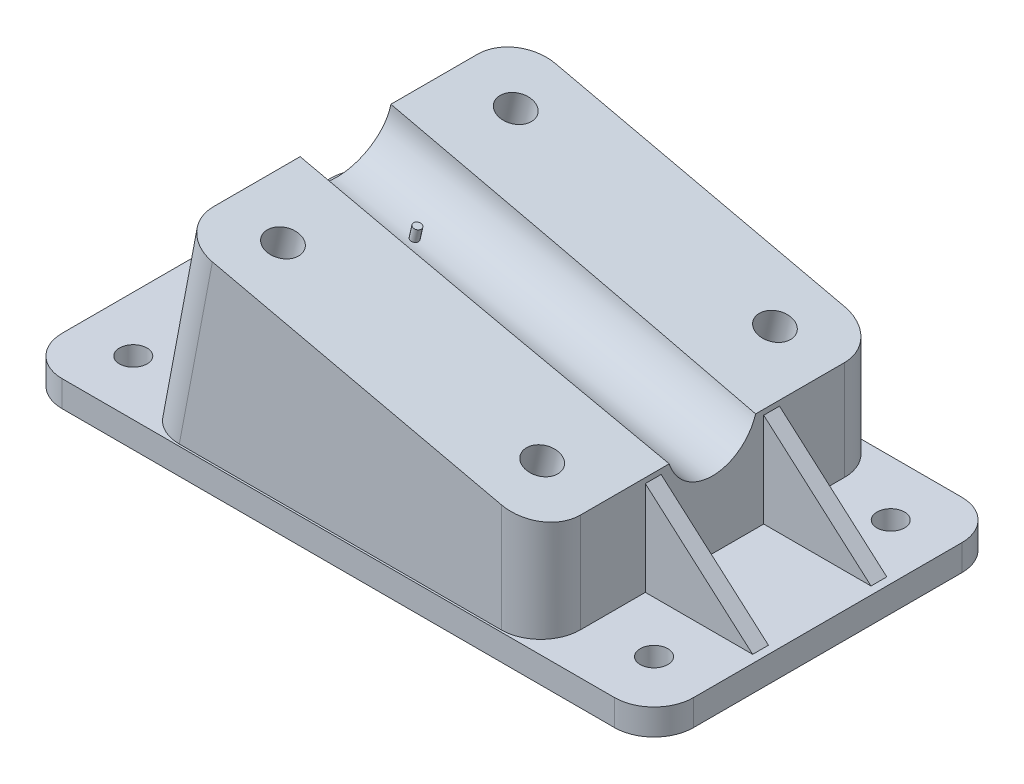
SolidWorks part; units mm, degrees
ref_plane "Front Plane" through (0, 0, 0) normal (0, 0, 1) x (1, 0, 0)
ref_plane "Top Plane" through (0, 0, 0) normal (0, 1, 0) x (1, 0, 0)
ref_plane "Right Plane" through (0, 0, 0) normal (1, 0, 0) x (0, 0, -1)
sketch "Sketch2" plane through (0, 0, 0) normal (0, 1, 0) x (1, 0, 0)
  line L1 (-40, -22) -> (40, -22)
  line L2 (-40, -22) -> (-40, 22)
  line L3 (-40, 22) -> (40, 22)
  line L4 (40, -22) -> (40, 22)
  line L5 (-40, -22) -> (40, 22) construction
  line L6 (-40, 22) -> (40, -22) construction
  point P0 (0, 0)
  dimension "D1" = 80
  dimension "D2" = 44
extrude "Boss-Extrude1" add sketch "Sketch2" along normal blind 3.3
fillet "Fillet1" radius 5 4 edges at (-40, 1.65, 22) (-40, 1.65, -22) (40, 1.65, -22) (40, 1.65, 22)
sketch "Sketch3" plane through (0, 3.3, 0) normal (0, 1, 0) x (1, 0, 0)
  line L1 (40, -17) -> (40, 17) construction
  line L2 (-35, -22) -> (35, -22) construction
  circle A6 centre (33, -15) radius 1.75
  dimension "D1" = 7
  dimension "D2" = 7
  dimension "D3" = 3.5
extrude "Cut-Extrude1" cut sketch "Sketch3" against normal through all
mirror "Mirror1" about plane through (0, 0, 0) normal (0, 0, 1) of "Cut-Extrude1"
mirror "Mirror2" about plane through (0, 0, 0) normal (1, 0, 0) of "Mirror1", "Cut-Extrude1"
sketch "Sketch4" plane through (0, 0, 0) normal (0, 0, 1) x (1, 0, 0)
  line L0 (-25.5, 3.3) -> (-21.1, 26.5)
  line L1 (-35, 3.3) -> (35, 3.3) construction
  line L4 (25.4, 3.3) -> (-25.5, 3.3)
  line L5 (-40, 3.3) -> (-40, 8.6486) construction
  line L6 (40, 3.3) -> (40, 9.0776) construction
  line L7 (25.4, 15.9) -> (25.4, 3.3)
  line L8 (-21.1, 26.5) -> (25.4, 15.9)
  dimension "D1" = 14.5
  dimension "D2" = 14.6
  dimension "D3" = 23.2
  dimension "D4" = 46.5
  dimension "D5" = 12.6
extrude "Boss-Extrude2" add sketch "Sketch4" along normal mid plane 43.5
fillet "Fillet2" radius 5 4 edges at (-23.3, 14.9, -21.75) (25.4, 9.6, -21.75) (25.4, 9.6, 21.75) (-23.3, 14.9, 21.75)
sketch "Sketch9" plane through (-25.2188, 4.7829, 0) normal (-0.9825, 0.1863, 0) x (0, 0, 1)
  line L0 (16.75, 22.1043) -> (-16.75, 22.1043) construction
  line L2 (-5.75, 22.1043) -> (5.75, 22.1043)
  arc A0 (5.75, 22.1043) -> (-5.75, 22.1043) centre (0, 22.1043) cw
  dimension "D1" = 5.75
extrude "Cut-Extrude2" cut sketch "Sketch9" against normal through all
sketch "Sketch10" plane through (4.7002, 20.6187, 0) normal (0.2223, 0.975, 0) x (0.975, -0.2223, 0)
  line L1 (-26.462, 5.75) -> (-26.462, 16.75) construction
  circle A0 centre (-16.262, 0) radius 0.5
  dimension "D1" = 1
  dimension "D2" = 10.2
extrude "Boss-Extrude3" add sketch "Sketch10" along normal blind 2 from offset 5.75 offset against normal yes
sketch "Sketch12" plane through (0, 0, 0) normal (0, 0, 1) x (1, 0, 0)
  line L0 (-23.038, 16.2813) -> (-38.2527, 3.3)
  line L1 (-25.5, 3.3) -> (-21.1, 26.5) construction
  line L2 (-35, 3.3) -> (-40, 3.3) construction
  line L3 (-40, 0) -> (-40, 3.3) construction
  line L4 (-38.2527, 3.3) -> (-25.5, 3.3)
  line L5 (-25.5, 3.3) -> (-23.038, 16.2813)
  dimension "D1" = 20
  dimension "D2" = 1.7473
extrude "Boss-Extrude4" add sketch "Sketch12" along normal mid plane 2
ref_plane "Plane2" through (0, 0, 7.5) normal (0, 0, 1) x (1, 0, 0)
sketch "Sketch14" plane through (0, 0, 7.5) normal (0, 0, 1) x (1, 0, 0)
  line L0 (25.4, 15.2436) -> (39, 3.3)
  line L1 (25.4, 15.9) -> (25.4, 3.3) construction
  line L2 (-35, 3.3) -> (35, 3.3) construction
  line L3 (39, 3.3) -> (25.4, 3.3)
  line L4 (25.4, 3.3) -> (25.4, 15.2436)
  line L5 (40, 3.3) -> (40, 0) construction
  dimension "D1" = 18.1
  dimension "D2" = 1
extrude "Boss-Extrude5" add sketch "Sketch14" along normal mid plane 2
mirror "Mirror3" about plane through (0, 0, 0) normal (0, 0, 1) of "Boss-Extrude5"
sketch "Sketch15" plane through (4.7002, 20.6187, 0) normal (0.2223, 0.975, 0) x (0.975, -0.2223, 0)
  line L0 (-26.462, 5.75) -> (-26.462, 16.75) construction
  line L1 (16.1026, 21.75) -> (-21.4587, 21.75) construction
  line L2 (21.2308, 5.4773) -> (21.2308, 16.75) construction
  circle A0 centre (-19.462, 14.75) radius 2.032
  circle A1 centre (14.2308, 14.75) radius 2.032
  dimension "D1" = 4.064
  dimension "D2" = 7
  dimension "D3" = 7
  dimension "D4" = 7
  dimension "D5" = 7
extrude "Cut-Extrude3" cut sketch "Sketch15" against normal blind 7.5
mirror "Mirror4" about plane through (0, 0, 0) normal (0, 0, 1) of "Cut-Extrude3"
